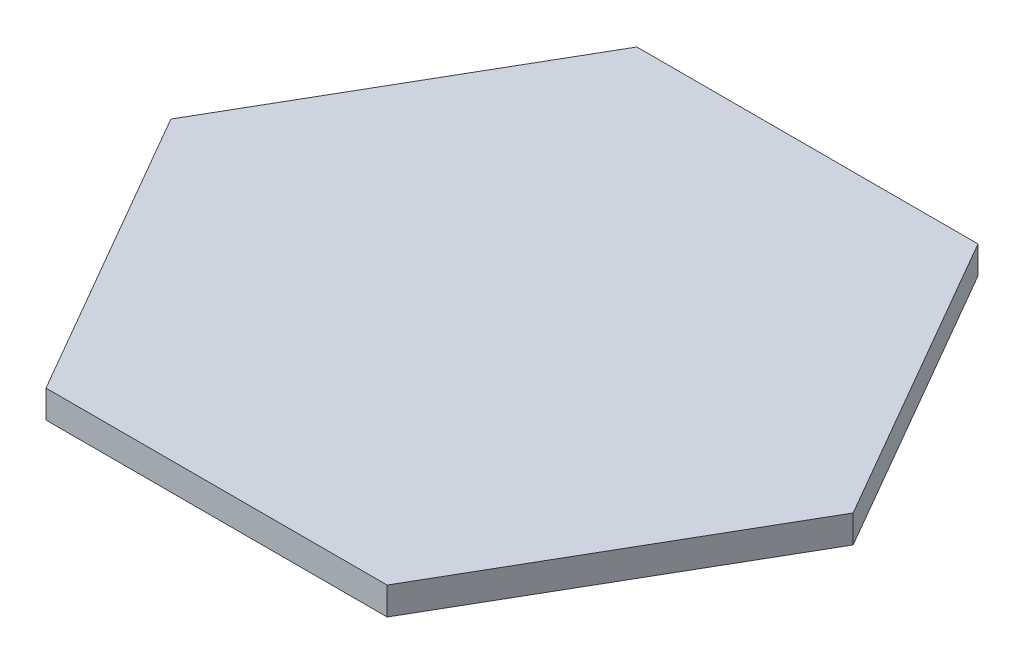
SolidWorks part; units mm, degrees
material "Oak"
ref_plane "Front Plane" through (0, 0, 0) normal (0, 0, 1) x (1, 0, 0)
ref_plane "Top Plane" through (0, 0, 0) normal (0, 1, 0) x (1, 0, 0)
ref_plane "Right Plane" through (0, 0, 0) normal (1, 0, 0) x (0, 0, -1)
sketch "Sketch1" plane through (0, 0, 0) normal (0, 1, 0) x (1, 0, 0)
  line L1 (-234.6351, 0) -> (-117.3176, -203.2)
  line L2 (-117.3176, -203.2) -> (117.3176, -203.2)
  line L3 (117.3176, -203.2) -> (234.6351, 0)
  line L4 (234.6351, 0) -> (117.3176, 203.2)
  line L5 (117.3176, 203.2) -> (-117.3176, 203.2)
  line L6 (-117.3176, 203.2) -> (-234.6351, 0)
  circle A0 centre (0, 0) radius 203.2 construction
  dimension "D1" = 406.4
extrude "Boss-Extrude1" add sketch "Sketch1" along normal blind 19.05
